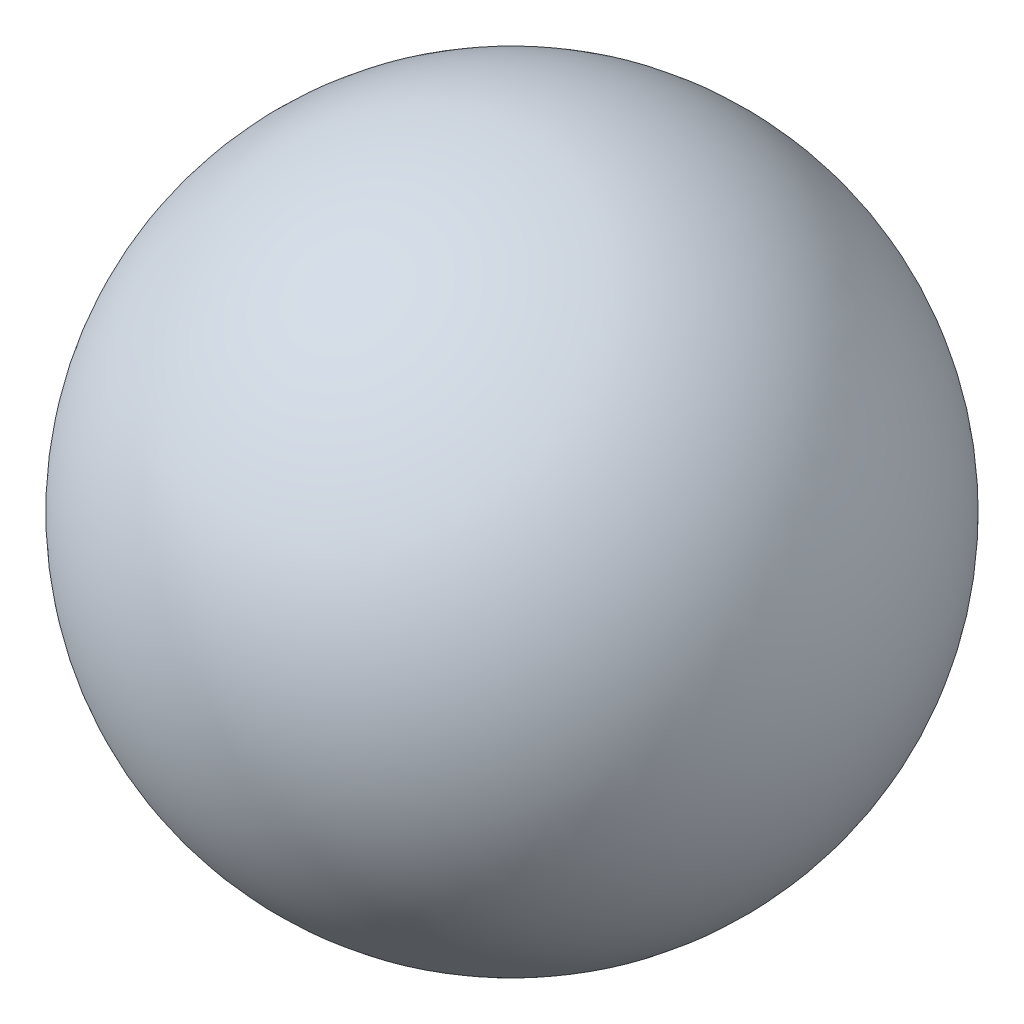
SolidWorks part; units mm, degrees
ref_plane "Front Plane" through (0, 0, 0) normal (0, 0, 1) x (1, 0, 0)
ref_plane "Top Plane" through (0, 0, 0) normal (0, 1, 0) x (1, 0, 0)
ref_plane "Right Plane" through (0, 0, 0) normal (1, 0, 0) x (0, 0, -1)
sketch "Sketch1" plane through (0, 0, 0) normal (0, 0, 1) x (1, 0, 0)
  line L0 (0, 0) -> (0, 12.5)
  line L1 (0, 0) -> (0, -12.5)
  arc A0 (0, 12.5) -> (0, -12.5) centre (0, 0) ccw
  dimension "D1" = 25
revolve "Revolve1" add sketch "Sketch1" angle 360 about L0
